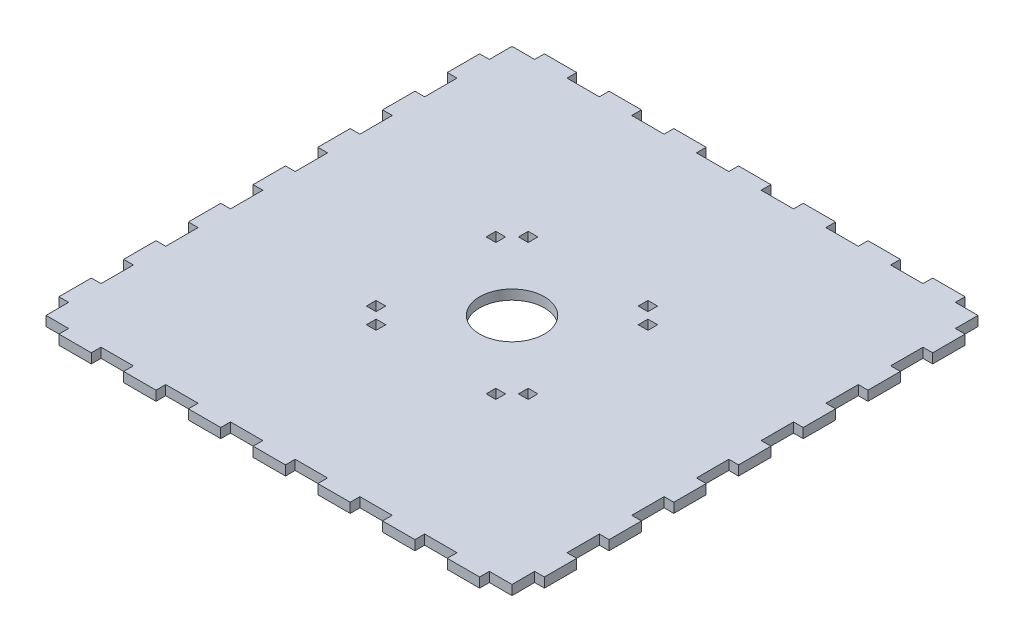
SolidWorks part; units mm, degrees
ref_plane "Alzado" through (0, 0, 0) normal (0, 0, 1) x (1, 0, 0)
ref_plane "Planta" through (0, 0, 0) normal (0, 1, 0) x (1, 0, 0)
ref_plane "Vista lateral" through (0, 0, 0) normal (1, 0, 0) x (0, 0, -1)
sketch "Croquis1" plane through (0, 0, 0) normal (0, 1, 0) x (1, 0, 0)
  line L1 (-72, -72) -> (-65, -72)
  line L2 (-72, -72) -> (-72, -65)
  line L3 (-72, 72) -> (-65, 72)
  line L4 (72, -72) -> (72, -65)
  line L5 (-72, -72) -> (72, 72) construction
  line L6 (-72, 72) -> (72, -72) construction
  line L7 (-72, -65) -> (-75, -65)
  line L9 (-72, -55) -> (-75, -55)
  line L10 (-75, -65) -> (-75, -55)
  line L11 (-72, -45) -> (-75, -45)
  line L12 (-75, -45) -> (-75, -35)
  line L13 (-72, -35) -> (-75, -35)
  line L15 (-72, -25) -> (-75, -25)
  line L16 (-75, -25) -> (-75, -15)
  line L17 (-72, -15) -> (-75, -15)
  line L19 (-72, -5) -> (-75, -5)
  line L20 (-75, -5) -> (-75, 5)
  line L21 (-72, 5) -> (-75, 5)
  line L23 (-72, 15) -> (-75, 15)
  line L24 (-75, 15) -> (-75, 25)
  line L25 (-72, 25) -> (-75, 25)
  line L27 (-72, 35) -> (-75, 35)
  line L28 (-75, 35) -> (-75, 45)
  line L29 (-72, 45) -> (-75, 45)
  line L31 (-72, 55) -> (-75, 55)
  line L32 (-75, 55) -> (-75, 65)
  line L33 (-72, 65) -> (-75, 65)
  line L34 (0, 0) -> (0, 55) construction
  line L35 (0, 0) -> (38.3292, 0) construction
  line L36 (72, -55) -> (75, -55)
  line L37 (75, -65) -> (75, -55)
  line L38 (72, -65) -> (75, -65)
  line L40 (72, -45) -> (75, -45)
  line L41 (75, -45) -> (75, -35)
  line L42 (72, -35) -> (75, -35)
  line L44 (72, -25) -> (75, -25)
  line L45 (75, -25) -> (75, -15)
  line L46 (72, -15) -> (75, -15)
  line L48 (72, -5) -> (75, -5)
  line L49 (75, -5) -> (75, 5)
  line L50 (72, 5) -> (75, 5)
  line L52 (72, 15) -> (75, 15)
  line L53 (75, 15) -> (75, 25)
  line L54 (72, 25) -> (75, 25)
  line L56 (72, 35) -> (75, 35)
  line L57 (75, 35) -> (75, 45)
  line L58 (72, 45) -> (75, 45)
  line L60 (72, 55) -> (75, 55)
  line L61 (75, 55) -> (75, 65)
  line L62 (72, 65) -> (75, 65)
  line L64 (-45, 72) -> (-45, 75)
  line L66 (-65, 72) -> (-65, 75)
  line L67 (-65, 75) -> (-55, 75)
  line L68 (-55, 72) -> (-55, 75)
  line L70 (-35, 72) -> (-35, 75)
  line L71 (-45, 75) -> (-35, 75)
  line L72 (-25, 72) -> (-25, 75)
  line L74 (-15, 72) -> (-15, 75)
  line L75 (-25, 75) -> (-15, 75)
  line L76 (-5, 72) -> (-5, 75)
  line L78 (5, 72) -> (5, 75)
  line L79 (-5, 75) -> (5, 75)
  line L80 (15, 72) -> (15, 75)
  line L82 (25, 72) -> (25, 75)
  line L83 (15, 75) -> (25, 75)
  line L84 (35, 72) -> (35, 75)
  line L86 (45, 72) -> (45, 75)
  line L87 (35, 75) -> (45, 75)
  line L88 (55, 72) -> (55, 75)
  line L90 (65, 72) -> (65, 75)
  line L91 (55, 75) -> (65, 75)
  line L92 (55, -75) -> (65, -75)
  line L93 (65, -72) -> (65, -75)
  line L95 (55, -72) -> (55, -75)
  line L96 (35, -75) -> (45, -75)
  line L97 (45, -72) -> (45, -75)
  line L99 (35, -72) -> (35, -75)
  line L100 (15, -75) -> (25, -75)
  line L101 (25, -72) -> (25, -75)
  line L103 (15, -72) -> (15, -75)
  line L104 (-5, -75) -> (5, -75)
  line L105 (5, -72) -> (5, -75)
  line L107 (-5, -72) -> (-5, -75)
  line L108 (-25, -75) -> (-15, -75)
  line L109 (-15, -72) -> (-15, -75)
  line L111 (-25, -72) -> (-25, -75)
  line L112 (-45, -75) -> (-35, -75)
  line L113 (-35, -72) -> (-35, -75)
  line L115 (-55, -72) -> (-55, -75)
  line L116 (-65, -75) -> (-55, -75)
  line L117 (-65, -72) -> (-65, -75)
  line L119 (-45, -72) -> (-45, -75)
  line L120 (-55, 72) -> (-45, 72)
  line L121 (-35, 72) -> (-25, 72)
  line L122 (-15, 72) -> (-5, 72)
  line L123 (5, 72) -> (15, 72)
  line L124 (25, 72) -> (35, 72)
  line L125 (45, 72) -> (55, 72)
  line L126 (65, 72) -> (72, 72)
  line L127 (72, 65) -> (72, 72)
  line L128 (72, 45) -> (72, 55)
  line L129 (72, 25) -> (72, 35)
  line L130 (72, 5) -> (72, 15)
  line L131 (72, -15) -> (72, -5)
  line L132 (72, -35) -> (72, -25)
  line L133 (72, -55) -> (72, -45)
  line L134 (65, -72) -> (72, -72)
  line L135 (45, -72) -> (55, -72)
  line L136 (25, -72) -> (35, -72)
  line L137 (5, -72) -> (15, -72)
  line L138 (-15, -72) -> (-5, -72)
  line L139 (-35, -72) -> (-25, -72)
  line L140 (-55, -72) -> (-45, -72)
  line L141 (-72, -55) -> (-72, -45)
  line L142 (-72, -35) -> (-72, -25)
  line L143 (-72, -15) -> (-72, -5)
  line L144 (-72, 5) -> (-72, 15)
  line L145 (-72, 25) -> (-72, 35)
  line L146 (-72, 45) -> (-72, 55)
  line L147 (-72, 65) -> (-72, 72)
  line L148 (20, 22) -> (17, 22)
  line L149 (-20, 25) -> (-17, 25)
  line L150 (-20, 25) -> (-20, 22)
  line L151 (-20, 22) -> (-17, 22)
  line L152 (-17, 25) -> (-17, 22)
  line L153 (-20, 25) -> (-17, 22) construction
  line L154 (-20, 22) -> (-17, 25) construction
  line L155 (-25, 20) -> (-22, 20)
  line L156 (-25, 20) -> (-25, 17)
  line L157 (-25, 17) -> (-22, 17)
  line L158 (-22, 20) -> (-22, 17)
  line L159 (-25, 20) -> (-22, 17) construction
  line L160 (-25, 17) -> (-22, 20) construction
  line L161 (17, 25) -> (17, 22)
  line L162 (20, 25) -> (17, 25)
  line L163 (20, 25) -> (20, 22)
  line L164 (-25, -17) -> (-22, -17)
  line L165 (-22, -20) -> (-22, -17)
  line L166 (-25, -20) -> (-22, -20)
  line L167 (-25, -20) -> (-25, -17)
  line L168 (25, -20) -> (25, -17)
  line L169 (25, -20) -> (22, -20)
  line L170 (22, -20) -> (22, -17)
  line L171 (25, -17) -> (22, -17)
  line L172 (25, 17) -> (22, 17)
  line L173 (22, 20) -> (22, 17)
  line L174 (25, 20) -> (22, 20)
  line L175 (25, 20) -> (25, 17)
  line L176 (20, -25) -> (20, -22)
  line L177 (20, -25) -> (17, -25)
  line L178 (17, -25) -> (17, -22)
  line L179 (20, -22) -> (17, -22)
  line L180 (-20, -22) -> (-17, -22)
  line L181 (-17, -25) -> (-17, -22)
  line L182 (-20, -25) -> (-17, -25)
  line L183 (-20, -25) -> (-20, -22)
  line L184 (-20, 22) -> (-21.5, 22) construction
  circle A0 centre (0, 0) radius 10
  point P0 (0, 0)
  point P122 (-18.5, 23.5)
  point P127 (-23.5, 18.5)
  dimension "D13" = 20
  dimension "D1" = 144
  dimension "D2" = 144
  dimension "D3" = 3
  dimension "D4" = 10
  dimension "D5" = 7
  dimension "D7" = 10
  dimension "D8" = 7
  dimension "D9" = 10
  dimension "D10" = 3
  dimension "D12" = 10
  dimension "D14" = 3
  dimension "D15" = 3
  dimension "D16" = 3
  dimension "D17" = 3
  dimension "D18" = 23.5
  dimension "D19" = 18.5
  dimension "D20" = 18.5
  dimension "D21" = 23.5
  dimension "D22" = 1.5
  dimension "D6" = 7
  dimension "D11" = 7
extrude "Saliente-Extruir2" add sketch "Croquis1" along normal blind 3
